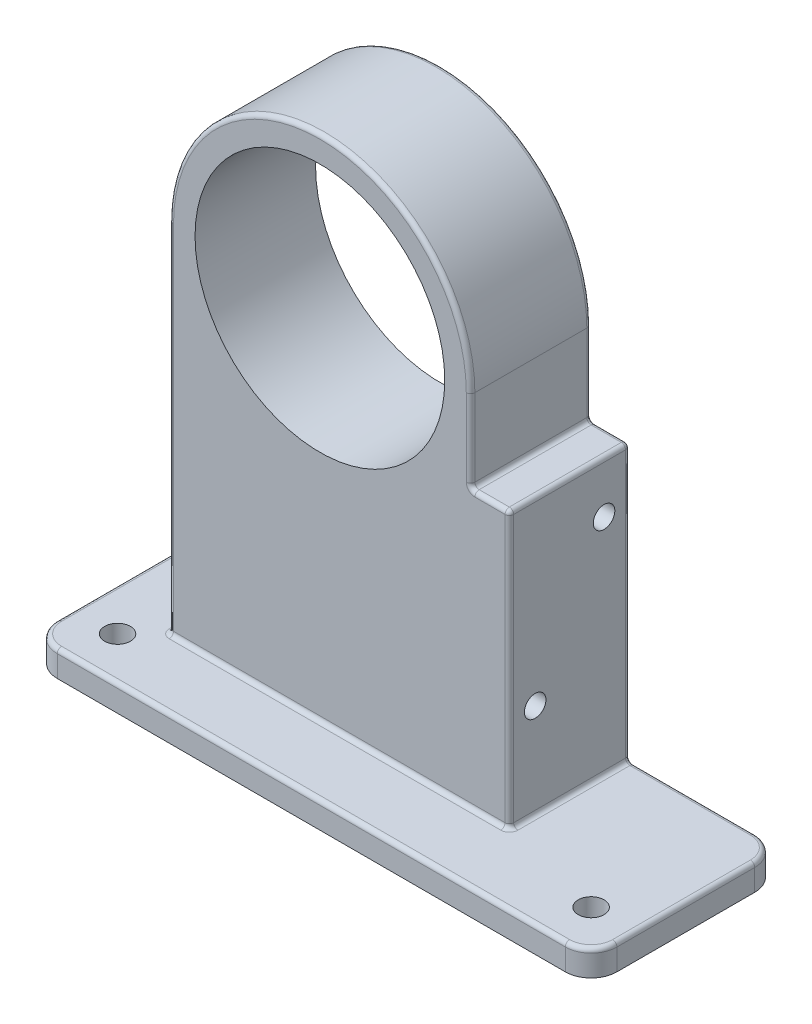
SolidWorks part; units mm, degrees
material "AISI 1020"
ref_plane "Front Plane" through (0, 0, 0) normal (0, 0, 1) x (1, 0, 0)
ref_plane "Top Plane" through (0, 0, 0) normal (0, 1, 0) x (1, 0, 0)
ref_plane "Right Plane" through (0, 0, 0) normal (1, 0, 0) x (0, 0, -1)
sketch "Sketch1" plane through (0, 0, 0) normal (0, 1, 0) x (1, 0, 0)
  line L1 (-29.5, -11) -> (29.5, -11)
  line L2 (-32.5, -8) -> (-32.5, 8)
  line L3 (-29.5, 11) -> (29.5, 11)
  line L4 (32.5, -8) -> (32.5, 8)
  line L5 (-32.5, -11) -> (32.5, 11) construction
  line L6 (-32.5, 11) -> (32.5, -11) construction
  circle A0 centre (-27.5, -6) radius 1.5
  circle A1 centre (27.5, -6) radius 1.5
  arc A2 (29.5, 11) -> (32.5, 8) centre (29.5, 8) cw
  arc A3 (29.5, -11) -> (32.5, -8) centre (29.5, -8) ccw
  arc A4 (-29.5, -11) -> (-32.5, -8) centre (-29.5, -8) cw
  arc A5 (-32.5, 8) -> (-29.5, 11) centre (-29.5, 8) cw
  point P0 (0, 0)
  dimension "D1" = 3
  dimension "D7" = 3
  dimension "D2" = 5
  dimension "D3" = 5
  dimension "D4" = 5
  dimension "D5" = 17
  dimension "D6" = 55
extrude "Boss-Extrude1" add sketch "Sketch1" along normal blind 3
sketch "Sketch3" plane through (0, 0, -11) normal (0, 0, -1) x (-1, 0, 0)
  line L0 (-29.5, 0) -> (29.5, 0) construction
  line L1 (32.5, 3) -> (32.5, 0) construction
  line L2 (24.5, 44.5) -> (24.5, 3)
  line L3 (-29.5, 3) -> (29.5, 3) construction
  line L4 (-10.5, 44.5) -> (-10.5, 35)
  line L5 (-10.5, 35) -> (-15, 35)
  line L6 (-15, 35) -> (-15, 3)
  circle A0 centre (7, 44.5) radius 14.5
  arc A1 (24.5, 44.5) -> (-10.5, 44.5) centre (7, 44.5) ccw
  line M5 (29.5, 3) -> (-29.5, 3)
  dimension "D1" = 29
  dimension "D2" = 17.5
  dimension "D3" = 44.5
  dimension "D4" = 25.5
  dimension "D5" = 4.5
  dimension "D6" = 32
extrude "Boss-Extrude2" add sketch "Sketch3" against normal blind 14 contours L2 A1 L4 L5 L6 A0 M5
sketch "Sketch4" plane through (15, 0, 0) normal (1, 0, 0) x (0, 0, -1)
  line L0 (-3, 35) -> (-3, 3) construction
  line L1 (-8, 3) -> (8, 3) construction
  point P0 (0, 14)
  point P1 (8, 29)
  dimension "D1" = 3
  dimension "D2" = 11
  dimension "D3" = 15
  dimension "D4" = 11
hole_wizard "M3x0.5 Tapped Hole1" positions "Sketch4" profile "Sketch5" tap size "M3x0.5" standard "ANSI Metric"
sketch "Sketch5" plane through (15, 14, 0) normal (0, 1, 0) x (0, 0, -1)
  line L0 (0, 0) -> (0, 11.5)
  line L1 (0, 11.5) -> (1.25, 10.7489)
  line L2 (1.25, 10.7489) -> (1.25, 0)
  line L5 (1.25, 0) -> (0, 0)
  line L10 (0, 11.5) -> (-1.25, 10.7489) construction
  line L11 (0, -6.35) -> (0, 107.95) construction
  dimension "Tap Drill Dia." = 2.5
  dimension "Tap Drill Depth" = 11.5
  dimension "Drill Angle" = 118
cosmetic thread "Hole Thread1" parameters "D1"=10, "D2"=3
cosmetic thread "Hole Thread2" parameters "D1"=10, "D2"=3
fillet "Fillet2" radius 0.5 24 edges at (-24.5, 3, -4) (-4.75, 3, 3) (-24.5, 23.75, 3) (10.5, 39.75, 3) (-24.5, 23.75, -11) (10.5, 39.75, -11) (-27, 3, -11) (-31.6213, 3, -10.1213) (-32.5, 3, 0) (-31.6213, 3, 10.1213) (22.25, 3, -11) (31.6213, 3, -10.1213) (32.5, 3, 0) (31.6213, 3, 10.1213) (15, 35, -4) (12.75, 35, 3) (10.5, 35, -4) (12.75, 35, -11) (-7, 62, 3) (-7, 62, -11) (15, 3, -4) (15, 19, -11) (15, 19, 3) (0, 3, 11)
